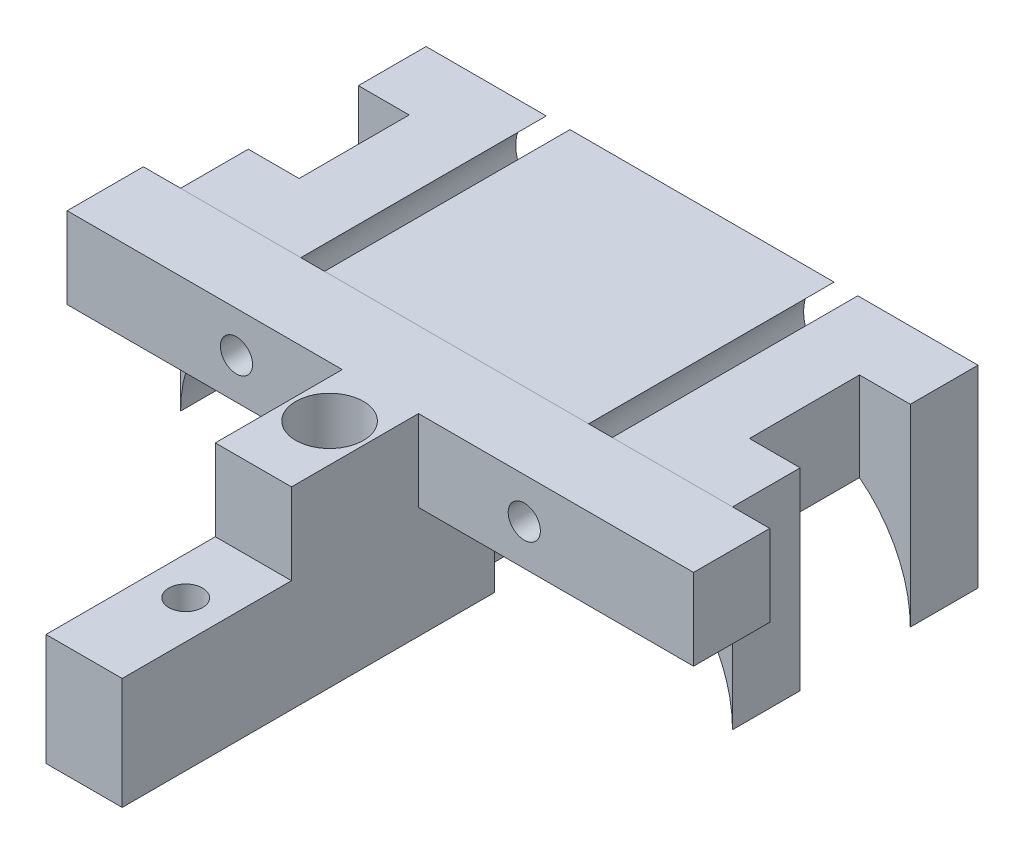
SolidWorks part; units mm, degrees
ref_plane "前视基准面" through (0, 0, 0) normal (0, 0, 1) x (1, 0, 0)
ref_plane "上视基准面" through (0, 0, 0) normal (0, 1, 0) x (1, 0, 0)
ref_plane "右视基准面" through (0, 0, 0) normal (1, 0, 0) x (0, 0, -1)
other "Configuration Table"
sketch "草图2" plane through (0, 0, 0) normal (0, 0, 1) x (1, 0, 0)
  line L0 (0, -2.4) -> (50000, -2.4) construction
  line L1 (0, 0) -> (37, 0)
  line L2 (0, 0) -> (0, -4.8)
  line L3 (0, -4.8) -> (37, -4.8)
  line L4 (37, 0) -> (37, -4.8)
  circle A0 centre (10, -2.4) radius 0.95
  circle A1 centre (27, -2.4) radius 0.95
  point P9 (0, -2.4)
  point P19 (37, -2.4)
  dimension "D4" = 1.9
  dimension "D5" = 1.9
  dimension "D1" = 37
  dimension "D2" = 4.8
  dimension "D3" = 10
  dimension "D6" = 10
extrude "凸台-拉伸1" add sketch "草图2" along normal blind 4
sketch "草图3" plane through (0, 0, 0) normal (0, 1, 0) x (1, 0, 0)
  line L0 (2.2, 0) -> (2.2, 4)
  line L1 (37, 0) -> (0, 0) construction
  line L2 (2.2, 4) -> (5.2, 4)
  line L3 (5.2, 4) -> (5.2, 10.5)
  line L4 (5.2, 10.5) -> (2.2, 10.5)
  line L5 (2.2, 10.5) -> (2.2, 14.5)
  line L6 (2.2, 14.5) -> (34.8, 14.5)
  line L7 (34.8, 14.5) -> (34.8, 10.5)
  line L8 (34.8, 10.5) -> (31.8, 10.5)
  line L9 (31.8, 10.5) -> (31.8, 4)
  line L10 (31.8, 4) -> (34.8, 4)
  line L11 (34.8, 4) -> (34.8, 0)
  line L12 (34.8, 0) -> (2.2, 0)
  line L13 (0, -4) -> (0, 0) construction
  line L14 (37, -4) -> (37, 0) construction
  dimension "D1" = 2.2
  dimension "D2" = 2.2
  dimension "D3" = 4
  dimension "D4" = 4
  dimension "D5" = 6.5
  dimension "D6" = 6.5
  dimension "D7" = 4
  dimension "D8" = 4
  dimension "D9" = 3
  dimension "D10" = 3
extrude "凸台-拉伸2" add sketch "草图3" against normal blind 11.4 separate body
sketch "草图4" plane through (0, 0, 0) normal (0, 0, 1) x (1, 0, 0)
  line L0 (10, -2.4) -> (10, -50002.4) construction
  line L1 (27, -2.4) -> (27, -50002.4) construction
  line L2 (2.2, -11.4) -> (34.8, -11.4) construction
  circle A0 centre (10, -11.4) radius 7.8
  circle A1 centre (27, -11.4) radius 7.8
extrude "切除-拉伸1" cut sketch "草图4" against normal blind 15
sketch "草图5" plane through (0, 0, 0) normal (0, 0, 1) x (1, 0, 0)
  circle A0 centre (10, -2.4) radius 2.5
  circle A1 centre (27, -2.4) radius 2.5
  dimension "D1" = 5
  dimension "D2" = 5
extrude "切除-拉伸2" cut sketch "草图5" against normal blind 15
sketch "草图6" plane through (0, 0, 0) normal (0, 0, 1) x (1, 0, 0)
  line L0 (37, 0) -> (0, 0) construction
  line L1 (17.8, -11.4) -> (19.2, -11.4) construction
  line L2 (16.25, 0) -> (20.75, 0)
  line L3 (16.25, 0) -> (16.25, -11.4)
  line L4 (16.25, -11.4) -> (20.75, -11.4)
  line L5 (20.75, 0) -> (20.75, -11.4)
  point P0 (18.5, 0)
  point P8 (18.5, 0)
  dimension "D1" = 4.5
extrude "凸台-拉伸3" add sketch "草图6" along normal blind 22
sketch "草图7" plane through (0, 0, 4) normal (0, 0, 1) x (1, 0, 0)
  line L1 (0, 0) -> (37, 0)
  line L2 (0, 0) -> (0, -4.8)
  line L3 (0, -4.8) -> (37, -4.8)
  line L4 (37, 0) -> (37, -4.8)
  circle A0 centre (10, -2.4) radius 0.95
  circle A1 centre (27, -2.4) radius 0.95
  dimension "D1" = 1.9
extrude "凸台-拉伸4" add sketch "草图7" along normal blind 0.5
sketch "草图8" plane through (0, 0, 0) normal (0, 1, 0) x (1, 0, 0)
  line L0 (16.25, -22) -> (20.75, -22)
  line L1 (20.75, -22) -> (20.75, -12)
  line L2 (20.75, -22) -> (20.75, -4.5) construction
  line L3 (20.75, -12) -> (16.25, -12)
  line L4 (16.25, -22) -> (16.25, -4.5) construction
  line L5 (16.25, -12) -> (16.25, -22)
  dimension "D1" = 10
extrude "切除-拉伸3" cut sketch "草图8" against normal blind 4.8
sketch "草图9" plane through (0, 0, 0) normal (0, 1, 0) x (1, 0, 0)
  line L0 (18.5, -12) -> (18.5, 49988) construction
  line L1 (20.75, -12) -> (16.25, -12) construction
  line L2 (14.5681, -4.5) -> (50014.5681, -4.5) construction
  line L5 (16.25, -4.5) -> (0, -4.5) construction
  line L6 (16.25, -22) -> (20.75, -22) construction
  circle A0 centre (18.5, -7.5) radius 0.95
  point P4 (18.5, -12)
  dimension "D2" = 1.9
  dimension "D1" = 14.5
extrude "切除-拉伸4" cut sketch "草图9" against normal blind 20
sketch "草图10" plane through (0, 0, 0) normal (0, 1, 0) x (1, 0, 0)
  circle A0 centre (18.5, -7.5) radius 2
  dimension "D1" = 4
extrude "切除-拉伸8" cut sketch "草图10" against normal blind 3
sketch "草图11" plane through (0, -4.8, 0) normal (0, 1, 0) x (1, 0, 0)
  line L0 (14.63, -16) -> (50014.63, -16) construction
  line L1 (18.5, -12) -> (18.5, -50012) construction
  line L2 (20.75, -12) -> (16.25, -12) construction
  line L3 (16.25, -22) -> (20.75, -22) construction
  circle A0 centre (18.5, -16) radius 1
  point P6 (18.5, -12)
  dimension "D2" = 2
  dimension "D1" = 6
extrude "切除-拉伸9" cut sketch "草图11" against normal blind 13
